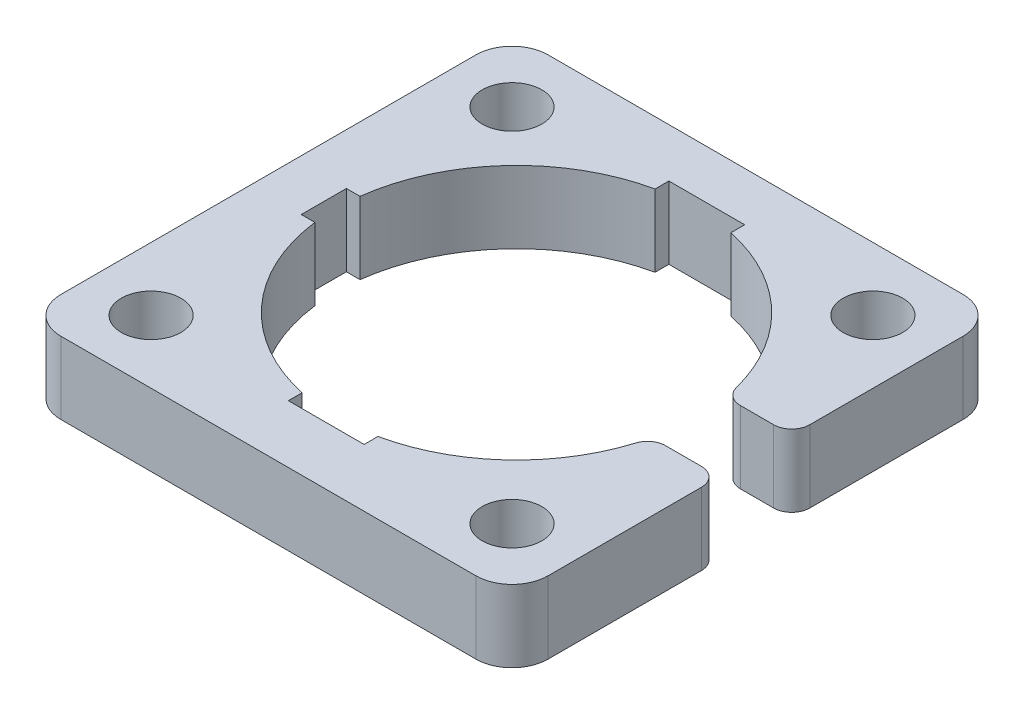
SolidWorks part; units mm, degrees
ref_plane "Front Plane" through (0, 0, 0) normal (0, 0, 1) x (1, 0, 0)
ref_plane "Top Plane" through (0, 0, 0) normal (0, 1, 0) x (1, 0, 0)
ref_plane "Right Plane" through (0, 0, 0) normal (1, 0, 0) x (0, 0, -1)
sketch "Sketch1" plane through (0, 0, 0) normal (0, 1, 0) x (1, 0, 0)
  line L1 (-13.5, -13.5) -> (13.5, -13.5)
  line L2 (-13.5, -13.5) -> (-13.5, 13.5)
  line L3 (-13.5, 13.5) -> (13.5, 13.5)
  line L4 (13.5, -13.5) -> (13.5, 13.5)
  line L5 (-13.5, -13.5) -> (13.5, 13.5) construction
  line L6 (-13.5, 13.5) -> (13.5, -13.5) construction
  line L7 (10, -10) -> (-10, -10) construction
  line L8 (10, -10) -> (10, 10) construction
  line L9 (10, 10) -> (-10, 10) construction
  line L10 (-10, -10) -> (-10, 10) construction
  line L11 (10, -10) -> (-10, 10) construction
  line L12 (10, 10) -> (-10, -10) construction
  circle A0 centre (10, 10) radius 1.65
  circle A1 centre (10, -10) radius 1.65
  circle A2 centre (-10, -10) radius 1.65
  circle A3 centre (-10, 10) radius 1.65
  point P0 (0, 0)
  point P6 (0, 0)
  dimension "D3" = 3.3
  dimension "D1" = 27
  dimension "D2" = 27
  dimension "D4" = 20
  dimension "D5" = 20
extrude "Boss-Extrude1" add sketch "Sketch1" along normal blind 4
sketch "Sketch2" plane through (0, 4, 0) normal (0, 1, 0) x (1, 0, 0)
  line L0 (-9.9216, 1.5) -> (-10.6771, 1.5)
  line L1 (-10.6771, 1.5) -> (-10.6771, -1)
  line L2 (-10.6771, -1) -> (-9.9216, -1)
  line L3 (0, 0.25) -> (-10.6771, 0.25) construction
  line L4 (-2.1, -9.527) -> (-2.1, -10.2929)
  line L5 (-2.1, -10.2929) -> (2.1, -10.2929)
  line L6 (2.1, -10.2929) -> (2.1, -9.527)
  line L7 (0, 0.25) -> (0, -10.2929) construction
  line L8 (2.1, 10.7929) -> (2.1, 10.027)
  line L9 (-2.1, 10.7929) -> (2.1, 10.7929)
  line L10 (-2.1, 10.027) -> (-2.1, 10.7929)
  line L23 (-13.5, -13.5) -> (13.5, -13.5) construction
  line L24 (0, 0) -> (0, 0.25) construction
  line L26 (9.9216, 1.5) -> (10.6771, 1.5)
  line L27 (10.6771, 1.5) -> (10.6771, -1)
  line L28 (10.6771, -1) -> (9.9216, -1)
  arc A1 (-9.9216, -1) -> (-2.1, -9.527) centre (0, 0.25) ccw
  circle A2 centre (0, 0.25) radius 10.75 construction
  arc A3 (2.1, -9.527) -> (9.9216, -1) centre (0, 0.25) ccw
  arc A4 (-2.1, 10.027) -> (-9.9216, 1.5) centre (0, 0.25) ccw
  arc A5 (9.9216, 1.5) -> (2.1, 10.027) centre (0, 0.25) ccw
  dimension "D1" = 13.75
  dimension "D2" = 20
  dimension "D5" = 21.5
  dimension "D3" = 2.5
  dimension "D4" = 4.2
extrude "Cut-Extrude1" cut sketch "Sketch2" against normal through all
sketch "Sketch4" plane through (0, 4, 0) normal (0, 1, 0) x (1, 0, 0)
  circle A0 centre (10, 10) radius 3.25
  circle A1 centre (-10, 10) radius 3.25
  circle A2 centre (0, 0) radius 11.5
  dimension "D1" = 6.5
  dimension "D2" = 23
fillet "Fillet2" radius 2 4 edges at (13.5, 2, -13.5) (13.5, 2, 13.5) (-13.5, 2, 13.5) (-13.5, 2, -13.5)
sketch "Sketch5" plane through (0, 4, 0) normal (0, 1, 0) x (1, 0, 0)
  line L0 (0, 0) -> (3.6163, 0) construction
  line L1 (17.9421, -2) -> (3.6163, -2)
  line L2 (17.9421, -2) -> (17.9421, 2)
  line L3 (17.9421, 2) -> (3.6163, 2)
  line L4 (3.6163, -2) -> (3.6163, 2)
  dimension "D1" = 4
extrude "Cut-Extrude2" cut sketch "Sketch5" against normal through all
fillet "Fillet3" radius 1 4 edges at (13.5, 2, 2) (9.7436, 2, 2) (9.8457, 2, -2) (13.5, 2, -2)
